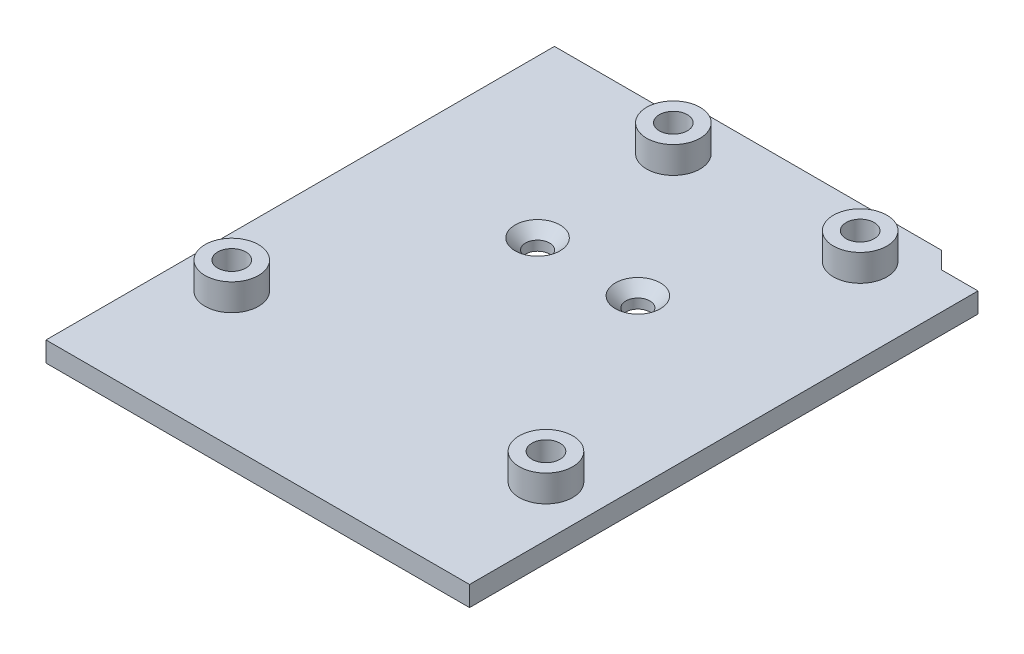
SolidWorks part; units mm, degrees
material "ABS"
ref_plane "Front Plane" through (0, 0, 0) normal (0, 0, 1) x (1, 0, 0)
ref_plane "Top Plane" through (0, 0, 0) normal (0, 1, 0) x (1, 0, 0)
ref_plane "Right Plane" through (0, 0, 0) normal (1, 0, 0) x (0, 0, -1)
sketch "Sketch1" plane through (0, 0, 0) normal (0, 1, 0) x (1, 0, 0)
  line L8 (5, -5) -> (5, 71.04)
  line L9 (5, 71.04) -> (-0.4689, 71.04)
  line L10 (-0.4689, 71.04) -> (-3.0089, 73.58)
  line L11 (-3.0089, 73.58) -> (-39.9171, 73.58)
  line L12 (-39.9171, 73.58) -> (-42.4571, 71.04)
  line L13 (-42.4571, 71.04) -> (-58.34, 71.04)
  line L14 (-58.34, 71.04) -> (-58.34, -5)
  line L15 (-58.34, -5) -> (5, -5)
  circle A0 centre (-50.8, 15.24) radius 1.5875
  circle A1 centre (-2.54, 13.97) radius 1.5875
  circle A2 centre (-7.62, 66.04) radius 1.5875
  circle A3 centre (-35.56, 66.04) radius 1.5875
extrude "Boss-Extrude1" add sketch "Sketch1" along normal blind 3
sketch "Sketch2" plane through (0, 3, 0) normal (0, 1, 0) x (1, 0, 0)
  circle A0 centre (-50.8, 15.24) radius 2.1
  circle A1 centre (-35.56, 66.04) radius 2.1
  circle A2 centre (-7.62, 66.04) radius 2.1
  circle A3 centre (-2.54, 13.97) radius 2.1
  dimension "D1" = 4.2
extrude "Cut-Extrude1" cut sketch "Sketch2" against normal through all
sketch "Sketch3" plane through (0, 3, 0) normal (0, 1, 0) x (1, 0, 0)
  circle A0 centre (-50.8, 15.24) radius 2.1
  circle A1 centre (-35.56, 66.04) radius 2.1
  circle A2 centre (-7.62, 66.04) radius 2.1
  circle A3 centre (-2.54, 13.97) radius 2.1
  circle A4 centre (-50.8, 15.24) radius 4
  circle A5 centre (-35.56, 66.04) radius 4
  circle A6 centre (-7.62, 66.04) radius 4
  circle A7 centre (-2.54, 13.97) radius 4
extrude "Boss-Extrude2" add sketch "Sketch3" along normal blind 4
hole_wizard "CSK for M3 Hex Socket Countersunk Cap Screw1" positions "Sketch4" profile "Sketch5" countersink size "M3" standard "ISO"
sketch "Sketch4" plane through (0, 3, 0) normal (0, 1, 0) x (1, 0, 0)
  point P0 (-34.7978, 44.9735)
  point P2 (-19.7978, 44.9735)
  dimension "D1" = 15
sketch "Sketch5" plane through (-34.7978, 3, -44.9735) normal (1, 0, 0) x (0, 0, 1)
  line L0 (0, 0) -> (0, 15.5215)
  line L1 (0, 15.5215) -> (1.8, 14.44)
  line L2 (1.8, 14.44) -> (1.8, 1.56)
  line L3 (1.8, 1.56) -> (3.36, 0)
  line L5 (3.36, 0) -> (0, 0)
  line L6 (-1.8, 1.56) -> (-3.36, 0) construction
  line L10 (0, 15.5215) -> (-1.8, 14.44) construction
  line L11 (0, -6.35) -> (0, 107.95) construction
  dimension "Hole Dia." = 3.6
  dimension "Hole Depth" = 14.44
  dimension "Near C'Sink Dia." = 6.72
  dimension "Near C'Sink Angle" = 90
  dimension "Drill Angle" = 118
